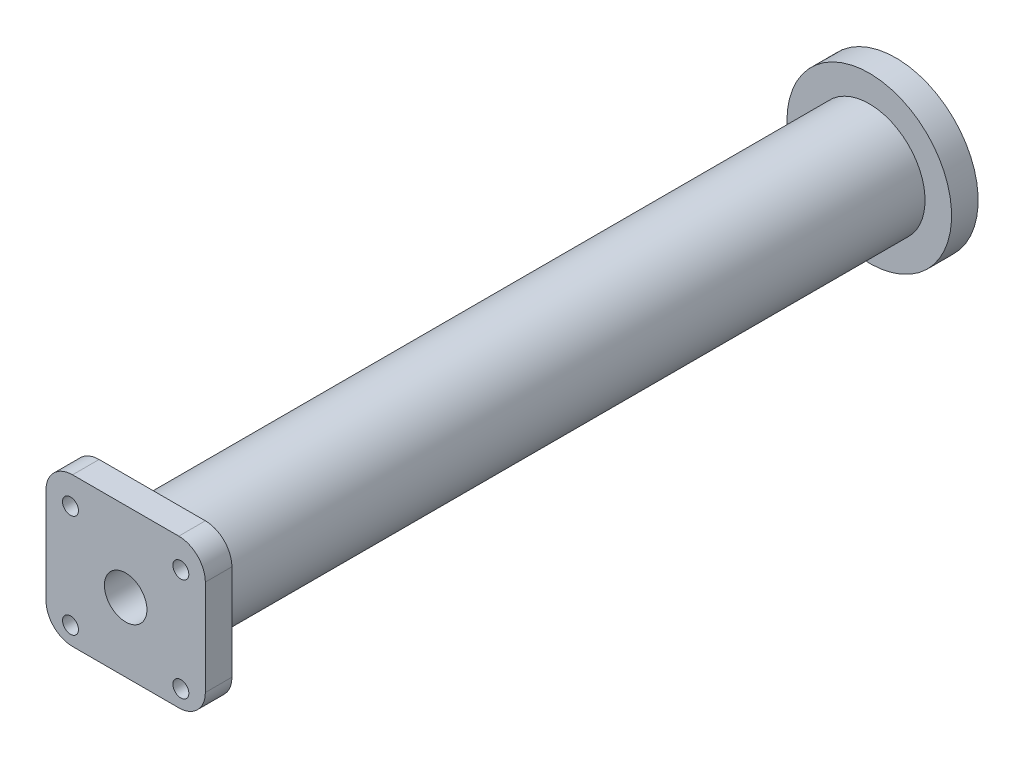
SolidWorks part; units mm, degrees
ref_plane "Front Plane" through (0, 0, 0) normal (0, 0, 1) x (1, 0, 0)
ref_plane "Top Plane" through (0, 0, 0) normal (0, 1, 0) x (1, 0, 0)
ref_plane "Right Plane" through (0, 0, 0) normal (1, 0, 0) x (0, 0, -1)
sketch "Sketch1" plane through (0, 0, 0) normal (0, 0, 1) x (1, 0, 0)
  circle A0 centre (0, 0) radius 4
  circle A1 centre (0, 0) radius 10.5
  dimension "D1" = 21
  dimension "D2" = 8
extrude "Boss-Extrude1" add sketch "Sketch1" along normal blind 140
sketch "Sketch2" plane through (0, 0, 140) normal (0, 0, 1) x (1, 0, 0)
  line L0 (-10.3883, 9.6957) -> (10.3883, -9.6957) construction
  line L1 (-15, 15) -> (15, 15)
  line L2 (-15, 15) -> (-15, -13)
  line L3 (-15, -13) -> (15, -13)
  line L4 (15, 15) -> (15, -13)
  line L5 (-15, 15) -> (15, -13) construction
  line L6 (-15, -13) -> (15, 15) construction
  circle A0 centre (-10.3883, 9.6957) radius 1.5
  circle A1 centre (10.3883, -9.6957) radius 1.5
  circle A2 centre (10.3883, 9.6957) radius 1.5
  circle A3 centre (-10.3883, -9.6957) radius 1.5
  circle A4 centre (0, 0) radius 4 construction
  circle A5 centre (0, 0) radius 4
  point P0 (0, 0)
  point P5 (0, 1)
  point P15 (0, 0)
  dimension "D3" = 3
  dimension "D1" = 28
  dimension "D2" = 30
  dimension "D4" = 14.21
  dimension "D5" = 13
extrude "Boss-Extrude2" add sketch "Sketch2" along normal blind 5
fillet "Fillet1" radius 5 4 edges at (15, -13, 142.5) (-15, -13, 142.5) (15, 15, 142.5) (-15, 15, 142.5)
sketch "Sketch3" plane through (0, 0, 0) normal (0, 0, -1) x (-1, 0, 0)
  circle A0 centre (0, 0) radius 10.5 construction
  circle A1 centre (0, 0) radius 10.5
extrude "Extrude-Thin1" add sketch "Sketch3" against normal blind 5 thin
